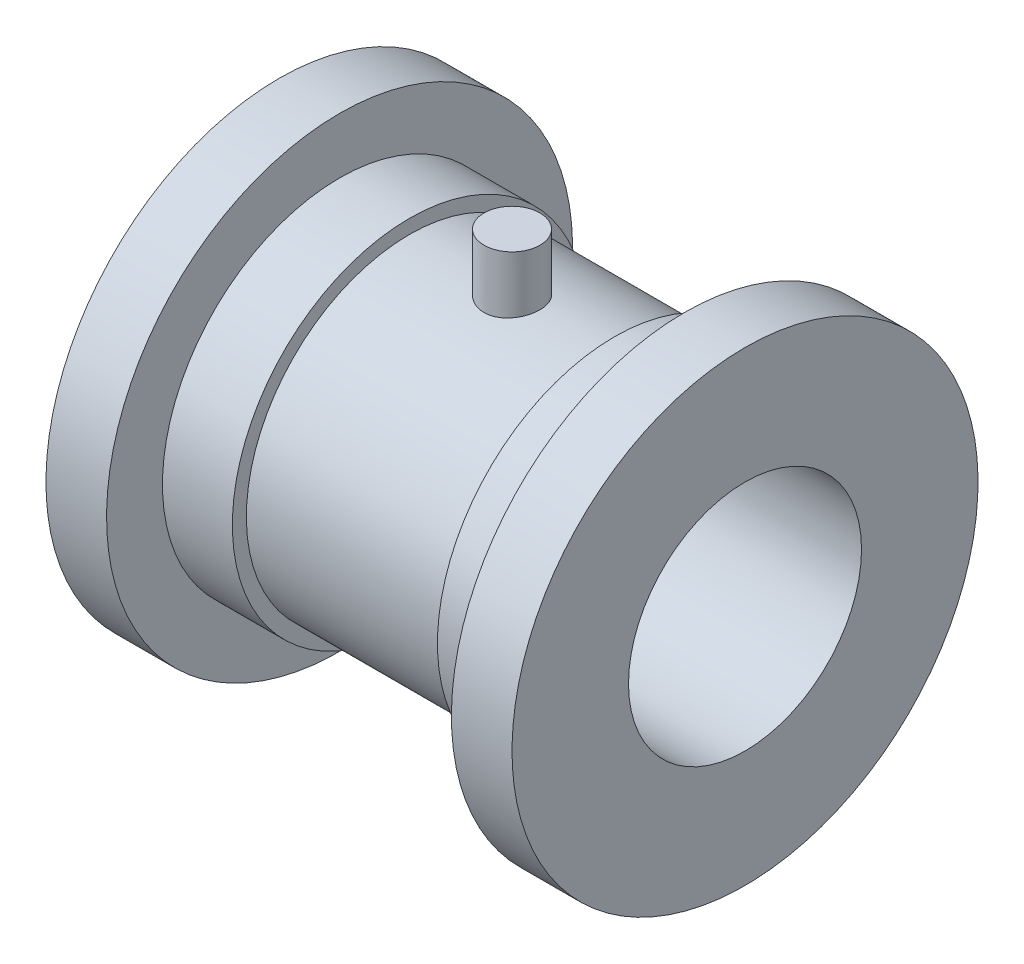
SolidWorks part; units mm, degrees
ref_plane "Front Plane" through (0, 0, 0) normal (0, 0, 1) x (1, 0, 0)
ref_plane "Top Plane" through (0, 0, 0) normal (0, 1, 0) x (1, 0, 0)
ref_plane "Right Plane" through (0, 0, 0) normal (1, 0, 0) x (0, 0, -1)
other "Center of Mass"
sketch "Sketch1" plane through (0, 0, 0) normal (0, 0, 1) x (1, 0, 0)
  line L0 (-25, 25) -> (-18.5, 25)
  line L1 (25, 0) -> (-25, 0)
  line L2 (-25, 12.5) -> (-25, 0)
  line L3 (11, 19) -> (11, 17.5)
  line L4 (25, 25) -> (18.5, 25)
  line L5 (-11, 17.5) -> (11, 17.5)
  line L6 (-18.5, 19) -> (-11, 19)
  line L7 (-11, 19) -> (-11, 17.5)
  line L8 (-25, 25) -> (-25, 12.5)
  line L9 (25, 12.5) -> (25, 0)
  line L10 (-18.5, 25) -> (-18.5, 19)
  line L11 (-25, 12.5) -> (25, 12.5)
  line L12 (18.5, 19) -> (11, 19)
  line L13 (18.5, 25) -> (18.5, 19)
  line L14 (25, 25) -> (25, 12.5)
  point P18 (0, 17.5)
  point P20 (0, 12.5)
revolve "Revolve1" add sketch "Sketch1" angle 360 about L1
sketch "Sketch2" plane through (0, 0, 0) normal (0, 1, 0) x (1, 0, 0)
  circle A0 centre (0, 0) radius 2
extrude "Cut-Extrude1" cut sketch "Sketch2" against normal blind 42
sketch "Sketch3" plane through (0, 0, 0) normal (0, 1, 0) x (1, 0, 0)
  circle A0 centre (0, 0) radius 3
extrude "Boss-Extrude1" add sketch "Sketch3" along normal blind 23.5
sketch "Sketch20" plane through (-25, 0, 0) normal (-1, 0, 0) x (0, 0, 1)
  circle A0 centre (0, 0) radius 12.5
extrude "Cut-Extrude2" cut sketch "Sketch20" against normal through all
